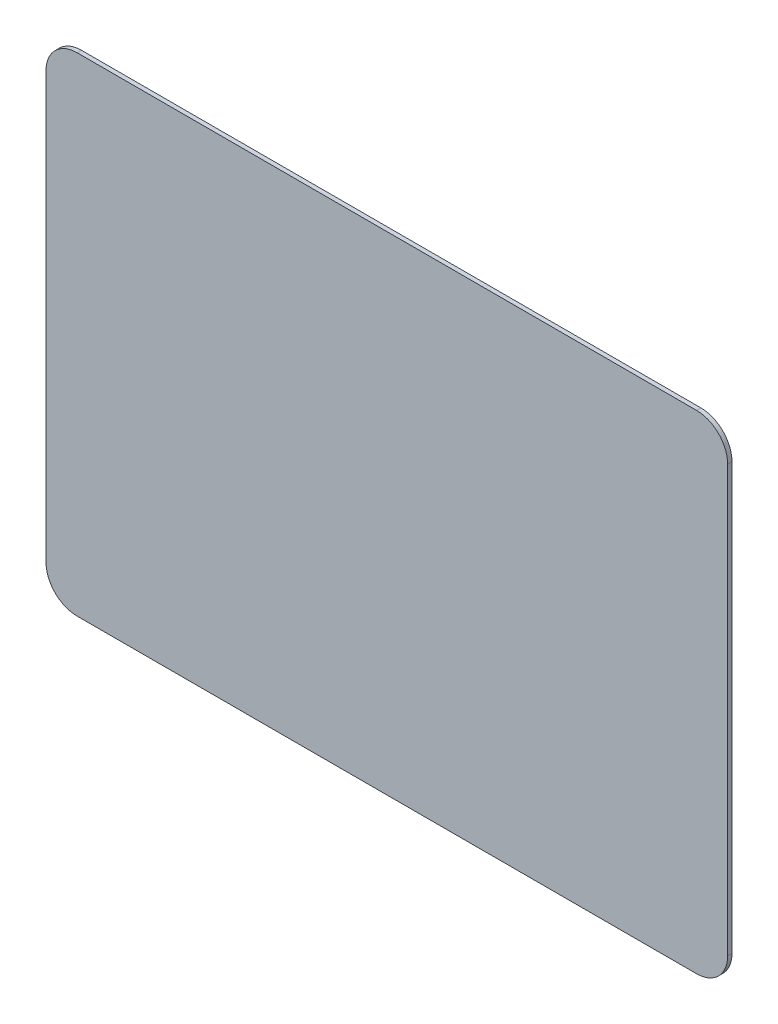
SolidWorks part; units mm, degrees
ref_plane "Front Plane" through (0, 0, 0) normal (0, 0, 1) x (1, 0, 0)
ref_plane "Top Plane" through (0, 0, 0) normal (0, 1, 0) x (1, 0, 0)
ref_plane "Right Plane" through (0, 0, 0) normal (1, 0, 0) x (0, 0, -1)
sketch "Sketch1" plane through (0, 0, 0) normal (0, 0, 1) x (1, 0, 0)
  line L0 (-177.4035, -145.1142) -> (151.5265, -145.1142)
  line L5 (-193.9135, -128.6042) -> (-193.9135, 97.4558)
  line L6 (-177.4035, 113.9658) -> (151.5265, 113.9658)
  line L7 (168.0365, -128.6042) -> (168.0365, 97.4558)
  arc A0 (-193.9135, -128.6042) -> (-177.4035, -145.1142) centre (-177.4035, -128.6042) ccw
  arc A1 (151.5265, -145.1142) -> (168.0365, -128.6042) centre (151.5265, -128.6042) ccw
  arc A2 (168.0365, 97.4558) -> (151.5265, 113.9658) centre (151.5265, 97.4558) ccw
  arc A3 (-177.4035, 113.9658) -> (-193.9135, 97.4558) centre (-177.4035, 97.4558) ccw
  dimension "D1" = 361.95
  dimension "D2" = 259.08
extrude "Boss-Extrude1" add sketch "Sketch1" along normal blind 2.286
